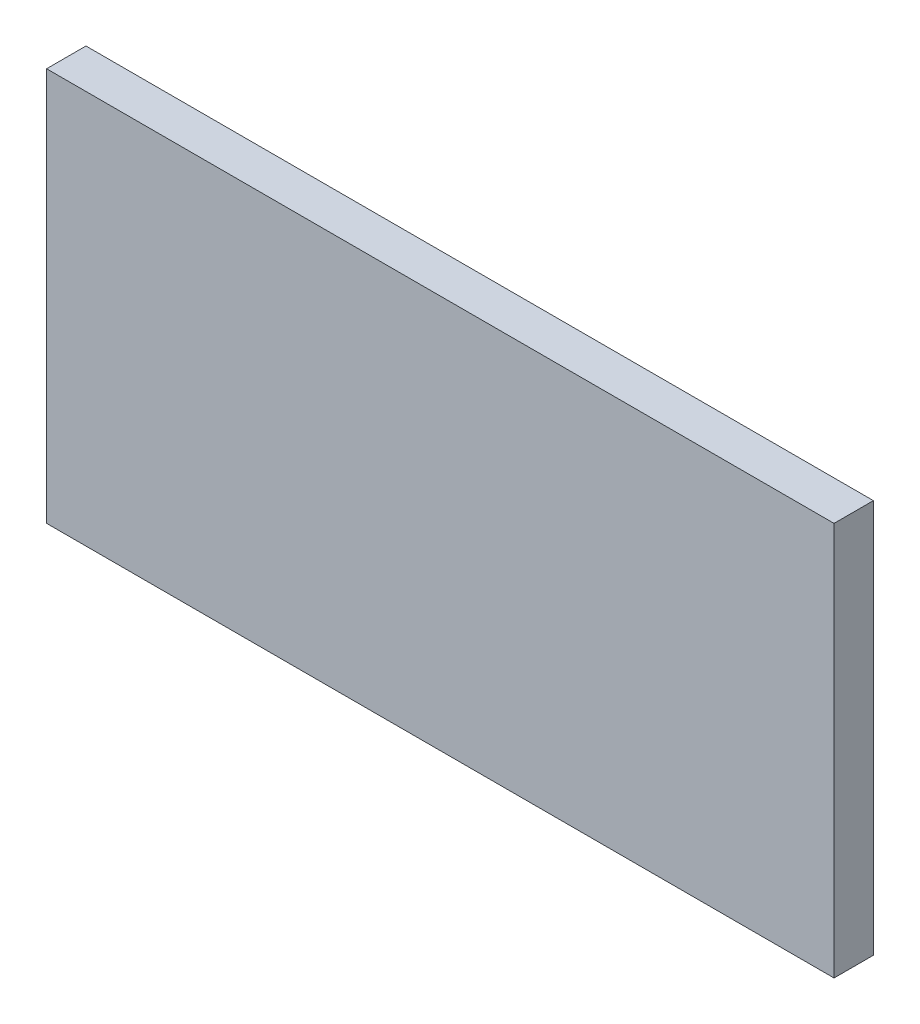
SolidWorks part; units mm, degrees
ref_plane "Front Plane" through (0, 0, 0) normal (0, 0, 1) x (1, 0, 0)
ref_plane "Top Plane" through (0, 0, 0) normal (0, 1, 0) x (1, 0, 0)
ref_plane "Right Plane" through (0, 0, 0) normal (1, 0, 0) x (0, 0, -1)
sketch "Sketch1" plane through (0, 0, 0) normal (0, 0, 1) x (1, 0, 0)
  line L1 (0, 0) -> (25.4, 0)
  line L2 (0, 0) -> (0, 12.7)
  line L3 (0, 12.7) -> (25.4, 12.7)
  line L4 (25.4, 0) -> (25.4, 12.7)
  dimension "D1" = 25.4
  dimension "D2" = 12.7
extrude "Boss-Extrude1" add sketch "Sketch1" along normal blind 1.27
